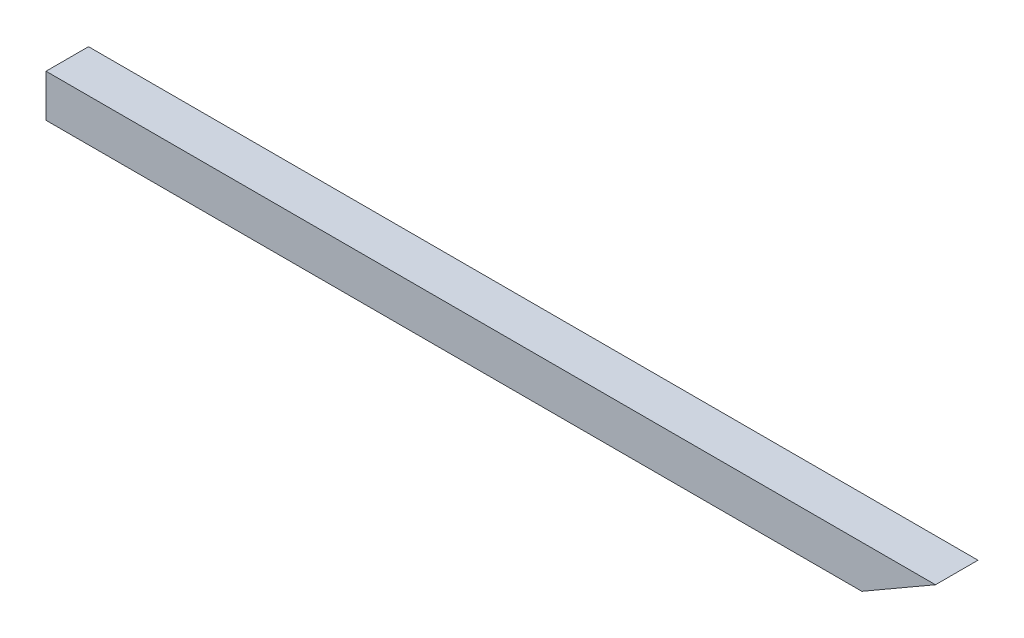
SolidWorks part; units mm, degrees
ref_plane "Front Plane" through (0, 0, 0) normal (0, 0, 1) x (1, 0, 0)
ref_plane "Top Plane" through (0, 0, 0) normal (0, 1, 0) x (1, 0, 0)
ref_plane "Right Plane" through (0, 0, 0) normal (1, 0, 0) x (0, 0, -1)
sketch "Sketch1" plane through (0, 0, 0) normal (0, 0, 1) x (1, 0, 0)
  line L0 (-37.8689, -10.2459) -> (345.9111, -10.2459)
  line L1 (-37.8689, 9.7541) -> (380.5522, 9.7541)
  line L2 (-37.8689, 9.7541) -> (-37.8689, -10.2459)
  line L3 (345.9111, -10.2459) -> (380.5522, 9.7541)
  dimension "D1" = 20
  dimension "D2" = 40
  dimension "D3" = 383.78
  dimension "D4" = 90
extrude "Boss-Extrude1" add sketch "Sketch1" along normal blind 20
